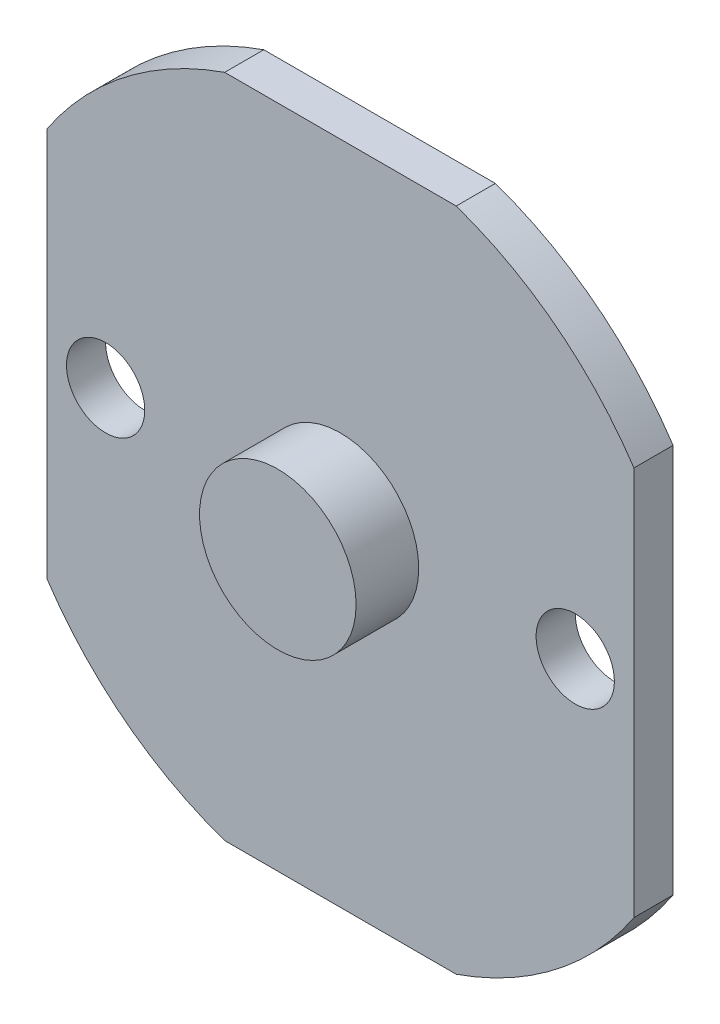
SolidWorks part; units mm, degrees
ref_plane "前视基准面" through (0, 0, 0) normal (0, 0, 1) x (1, 0, 0)
ref_plane "上视基准面" through (0, 0, 0) normal (0, 1, 0) x (1, 0, 0)
ref_plane "右视基准面" through (0, 0, 0) normal (1, 0, 0) x (0, 0, -1)
sketch "草图1" plane through (0, 0, 0) normal (0, 0, 1) x (1, 0, 0)
  circle A0 centre (0, 0) radius 9
  circle A1 centre (0, 0) radius 6 construction
  circle A2 centre (6, 0) radius 1
  circle A3 centre (-6, 0) radius 1
  dimension "D1" = 18
  dimension "D2" = 12
  dimension "D3" = 2
  dimension "D4" = 2
extrude "凸台-拉伸1" add sketch "草图1" along normal blind 1
sketch "草图2" plane through (0, 0, 1) normal (0, 0, 1) x (1, 0, 0)
  line L1 (-7.5, 8.5) -> (7.5, 8.5)
  line L2 (-7.5, 8.5) -> (-7.5, -8.5)
  line L3 (-7.5, -8.5) -> (7.5, -8.5)
  line L4 (7.5, 8.5) -> (7.5, -8.5)
  line L5 (-7.5, 8.5) -> (7.5, -8.5) construction
  line L6 (-7.5, -8.5) -> (7.5, 8.5) construction
  line L7 (-16.1947, 13.0603) -> (16.1947, 13.0603)
  line L8 (-16.1947, 13.0603) -> (-16.1947, -13.0603)
  line L9 (-16.1947, -13.0603) -> (16.1947, -13.0603)
  line L10 (16.1947, 13.0603) -> (16.1947, -13.0603)
  line L11 (-16.1947, 13.0603) -> (16.1947, -13.0603) construction
  line L12 (-16.1947, -13.0603) -> (16.1947, 13.0603) construction
  point P0 (0, 0)
  point P6 (0, 0)
  dimension "D1" = 17
  dimension "D2" = 15
extrude "切除-拉伸1" cut sketch "草图2" against normal blind 2
sketch "草图3" plane through (0, 0, 1) normal (0, 0, 1) x (1, 0, 0)
  circle A0 centre (0, 0) radius 2
extrude "凸台-拉伸2" add sketch "草图3" along normal blind 1.6
